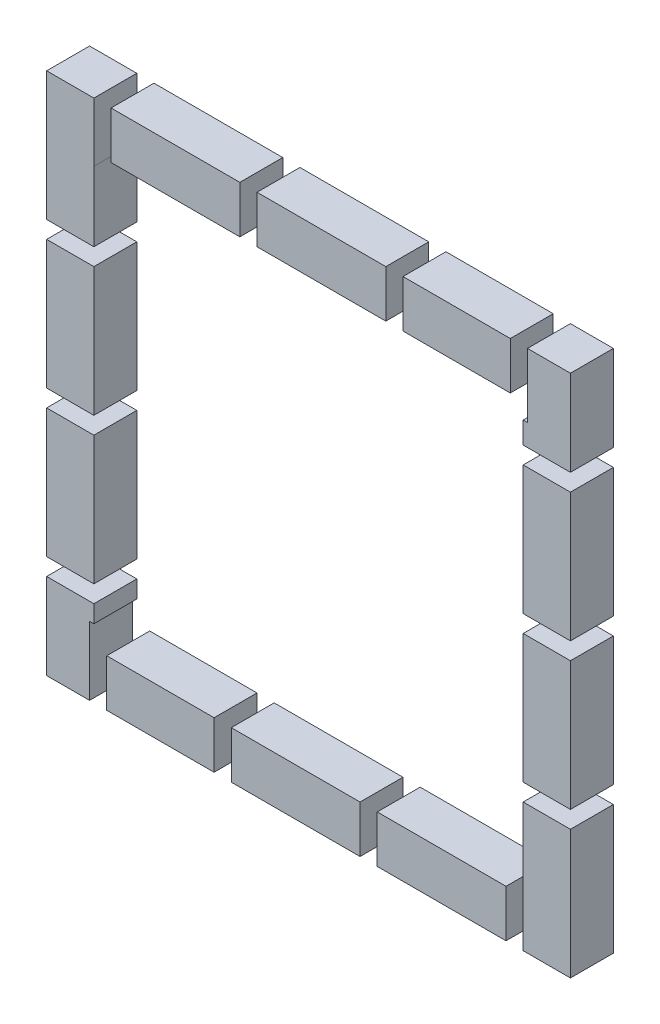
SolidWorks part; units mm, degrees
ref_plane "Front Plane" through (0, 0, 0) normal (0, 0, 1) x (1, 0, 0)
ref_plane "Top Plane" through (0, 0, 0) normal (0, 1, 0) x (1, 0, 0)
ref_plane "Right Plane" through (0, 0, 0) normal (1, 0, 0) x (0, 0, -1)
sketch "Sketch6" plane through (0, 0, 0) normal (0, 0, 1) x (1, 0, 0)
  line L1 (-199.4624, 105.1075) -> (-99.4624, 105.1075)
  line L2 (-199.4624, 105.1075) -> (-199.4624, 5.1075)
  line L3 (-199.4624, 5.1075) -> (-99.4624, 5.1075)
  line L4 (-99.4624, 105.1075) -> (-99.4624, 5.1075)
  line L5 (-210.4624, 116.1075) -> (-88.4624, 116.1075)
  line L6 (-210.4624, 116.1075) -> (-210.4624, -5.8925)
  line L7 (-210.4624, -5.8925) -> (-88.4624, -5.8925)
  line L8 (-88.4624, 116.1075) -> (-88.4624, -5.8925)
  dimension "D1" = 100
  dimension "D2" = 100
  dimension "D3" = 11
  dimension "D4" = 11
  dimension "D5" = 11
  dimension "D6" = 11
extrude "Boss-Extrude3" add sketch "Sketch6" along normal blind 10
sketch "Sketch7" plane through (0, 0, 0) normal (0, 0, 1) x (1, 0, 0)
  line L0 (-88.4624, 116.1075) -> (-210.4624, 116.1075) construction
  line L1 (-199.4634, 116.1075) -> (-195.4634, 116.1075)
  line L2 (-199.4634, 116.1075) -> (-199.4634, 102.3398)
  line L3 (-199.4634, 102.3398) -> (-195.4634, 102.3398)
  line L4 (-195.4634, 116.1075) -> (-195.4634, 102.3398)
  line L5 (-199.4624, 105.1075) -> (-199.4624, 5.1075) construction
  dimension "D1" = 0.001
  dimension "D2" = 4
extrude "Cut-Extrude2" cut sketch "Sketch7" along normal blind 10
sketch "Sketch8" plane through (0, 0, 0) normal (0, 0, 1) x (1, 0, 0)
  line L0 (-195.4634, 105.1075) -> (-195.4634, 116.1075) construction
  line L1 (-165.4634, 118.3465) -> (-161.4634, 118.3465)
  line L2 (-165.4634, 118.3465) -> (-165.4634, 103.3465)
  line L3 (-165.4634, 103.3465) -> (-161.4634, 103.3465)
  line L4 (-161.4634, 118.3465) -> (-161.4634, 103.3465)
  dimension "D1" = 30
  dimension "D2" = 4
  dimension "D3" = 15
extrude "Cut-Extrude3" cut sketch "Sketch8" along normal blind 10
sketch "Sketch9" plane through (0, 0, 0) normal (0, 0, 1) x (1, 0, 0)
  line L0 (-88.4624, 116.1075) -> (-161.4634, 116.1075) construction
  line L1 (-131.4634, 116.1075) -> (-127.4634, 116.1075)
  line L2 (-131.4634, 116.1075) -> (-131.4634, 98.1075)
  line L3 (-131.4634, 98.1075) -> (-127.4634, 98.1075)
  line L4 (-127.4634, 116.1075) -> (-127.4634, 98.1075)
  line L5 (-161.4634, 105.1075) -> (-161.4634, 116.1075) construction
  dimension "D1" = 30
  dimension "D2" = 4
  dimension "D3" = 18
extrude "Cut-Extrude4" cut sketch "Sketch9" along normal blind 10
sketch "Sketch10" plane through (0, 0, 0) normal (0, 0, 1) x (1, 0, 0)
  line L0 (-127.4634, 105.1075) -> (-127.4634, 116.1075) construction
  line L1 (-102.4634, 117.9441) -> (-98.4634, 117.9441)
  line L2 (-102.4634, 117.9441) -> (-102.4634, 101.1653)
  line L3 (-102.4634, 101.1653) -> (-98.4634, 101.1653)
  line L4 (-98.4634, 117.9441) -> (-98.4634, 101.1653)
  dimension "D1" = 25
  dimension "D2" = 4
extrude "Cut-Extrude5" cut sketch "Sketch10" along normal blind 10
sketch "Sketch11" plane through (0, 0, 0) normal (0, 0, 1) x (1, 0, 0)
  line L0 (-210.4624, -5.8925) -> (-88.4624, -5.8925) construction
  line L1 (-103.4634, 11.5666) -> (-99.4634, 11.5666)
  line L2 (-103.4634, 11.5666) -> (-103.4634, -5.8925)
  line L3 (-103.4634, -5.8925) -> (-99.4634, -5.8925)
  line L4 (-99.4634, 11.5666) -> (-99.4634, -5.8925)
  line L5 (-99.4624, 5.1075) -> (-99.4624, 101.1653) construction
  dimension "D1" = 0.001
  dimension "D2" = 4
extrude "Cut-Extrude7" cut sketch "Sketch11" along normal blind 10
sketch "Sketch12" plane through (0, 0, 0) normal (0, 0, 1) x (1, 0, 0)
  line L0 (-103.4634, 5.1075) -> (-103.4634, -5.8925) construction
  line L1 (-137.4634, 11.3988) -> (-133.4634, 11.3988)
  line L2 (-137.4634, 11.3988) -> (-137.4634, -10.4136)
  line L3 (-137.4634, -10.4136) -> (-133.4634, -10.4136)
  line L4 (-133.4634, 11.3988) -> (-133.4634, -10.4136)
  dimension "D1" = 30
  dimension "D2" = 4
extrude "Cut-Extrude9" cut sketch "Sketch12" along normal blind 10
sketch "Sketch13" plane through (0, 0, 0) normal (0, 0, 1) x (1, 0, 0)
  line L0 (-137.4634, 5.1075) -> (-137.4634, -5.8925) construction
  line L1 (-171.4634, 9.0845) -> (-167.4634, 9.0845)
  line L2 (-171.4634, 9.0845) -> (-171.4634, -8.4901)
  line L3 (-171.4634, -8.4901) -> (-167.4634, -8.4901)
  line L4 (-167.4634, 9.0845) -> (-167.4634, -8.4901)
  point P6 (-167.4634, 0.2972)
  dimension "D1" = 30
  dimension "D2" = 4
extrude "Cut-Extrude10" cut sketch "Sketch13" along normal blind 10
sketch "Sketch14" plane through (0, 0, 0) normal (0, 0, 1) x (1, 0, 0)
  line L0 (-171.4634, 5.1075) -> (-171.4634, -5.8925) construction
  line L1 (-200.4634, 10.0565) -> (-196.4634, 10.0565)
  line L2 (-200.4634, 10.0565) -> (-200.4634, -11.2526)
  line L3 (-200.4634, -11.2526) -> (-196.4634, -11.2526)
  line L4 (-196.4634, 10.0565) -> (-196.4634, -11.2526)
  dimension "D1" = 25
  dimension "D2" = 4
extrude "Cut-Extrude11" cut sketch "Sketch14" along normal blind 10
sketch "Sketch15" plane through (0, 0, 0) normal (0, 0, 1) x (1, 0, 0)
  line L0 (-199.4634, 116.1075) -> (-210.4624, 116.1075) construction
  line L1 (-212.5506, 86.1075) -> (-195.2685, 86.1075)
  line L2 (-212.5506, 86.1075) -> (-212.5506, 82.1075)
  line L3 (-212.5506, 82.1075) -> (-195.2685, 82.1075)
  line L4 (-195.2685, 86.1075) -> (-195.2685, 82.1075)
  dimension "D1" = 30
  dimension "D2" = 4
extrude "Cut-Extrude12" cut sketch "Sketch15" along normal blind 10
sketch "Sketch16" plane through (0, 0, 0) normal (0, 0, 1) x (1, 0, 0)
  line L0 (-210.4624, 82.1075) -> (-199.4624, 82.1075) construction
  line L1 (-213.5573, 52.1075) -> (-193.255, 52.1075)
  line L2 (-213.5573, 52.1075) -> (-213.5573, 48.1075)
  line L3 (-213.5573, 48.1075) -> (-193.255, 48.1075)
  line L4 (-193.255, 52.1075) -> (-193.255, 48.1075)
  dimension "D1" = 30
  dimension "D2" = 4
extrude "Cut-Extrude13" cut sketch "Sketch16" along normal blind 10
sketch "Sketch18" plane through (0, 0, 0) normal (0, 0, 1) x (1, 0, 0)
  line L0 (-210.4624, 48.1075) -> (-199.4624, 48.1075) construction
  line L1 (-212.7184, 18.1075) -> (-195.604, 18.1075)
  line L2 (-212.7184, 18.1075) -> (-212.7184, 14.1075)
  line L3 (-212.7184, 14.1075) -> (-195.604, 14.1075)
  line L4 (-195.604, 18.1075) -> (-195.604, 14.1075)
  dimension "D1" = 30
  dimension "D2" = 4
extrude "Cut-Extrude15" cut sketch "Sketch18" along normal blind 10
sketch "Sketch19" plane through (0, 0, 0) normal (0, 0, 1) x (1, 0, 0)
  line L0 (-99.4634, -5.8925) -> (-88.4624, -5.8925) construction
  line L1 (-101.7641, 28.1075) -> (-83.4752, 28.1075)
  line L2 (-101.7641, 28.1075) -> (-101.7641, 24.1075)
  line L3 (-101.7641, 24.1075) -> (-83.4752, 24.1075)
  line L4 (-83.4752, 28.1075) -> (-83.4752, 24.1075)
  dimension "D1" = 30
  dimension "D2" = 4
extrude "Cut-Extrude16" cut sketch "Sketch19" along normal blind 10
sketch "Sketch20" plane through (0, 0, 0) normal (0, 0, 1) x (1, 0, 0)
  line L0 (-99.4624, 28.1075) -> (-88.4624, 28.1075) construction
  line L1 (-101.8106, 62.1075) -> (-83.8573, 62.1075)
  line L2 (-101.8106, 62.1075) -> (-101.8106, 58.1075)
  line L3 (-101.8106, 58.1075) -> (-83.8573, 58.1075)
  line L4 (-83.8573, 62.1075) -> (-83.8573, 58.1075)
  dimension "D1" = 30
  dimension "D2" = 4
extrude "Cut-Extrude17" cut sketch "Sketch20" along normal blind 10
sketch "Sketch21" plane through (0, 0, 0) normal (0, 0, 1) x (1, 0, 0)
  line L0 (-88.4624, 62.1075) -> (-99.4624, 62.1075) construction
  line L1 (-104.663, 96.1075) -> (-81.5083, 96.1075)
  line L2 (-104.663, 96.1075) -> (-104.663, 92.1075)
  line L3 (-104.663, 92.1075) -> (-81.5083, 92.1075)
  line L4 (-81.5083, 96.1075) -> (-81.5083, 92.1075)
  dimension "D1" = 30
  dimension "D2" = 4
extrude "Cut-Extrude19" cut sketch "Sketch21" along normal blind 10
